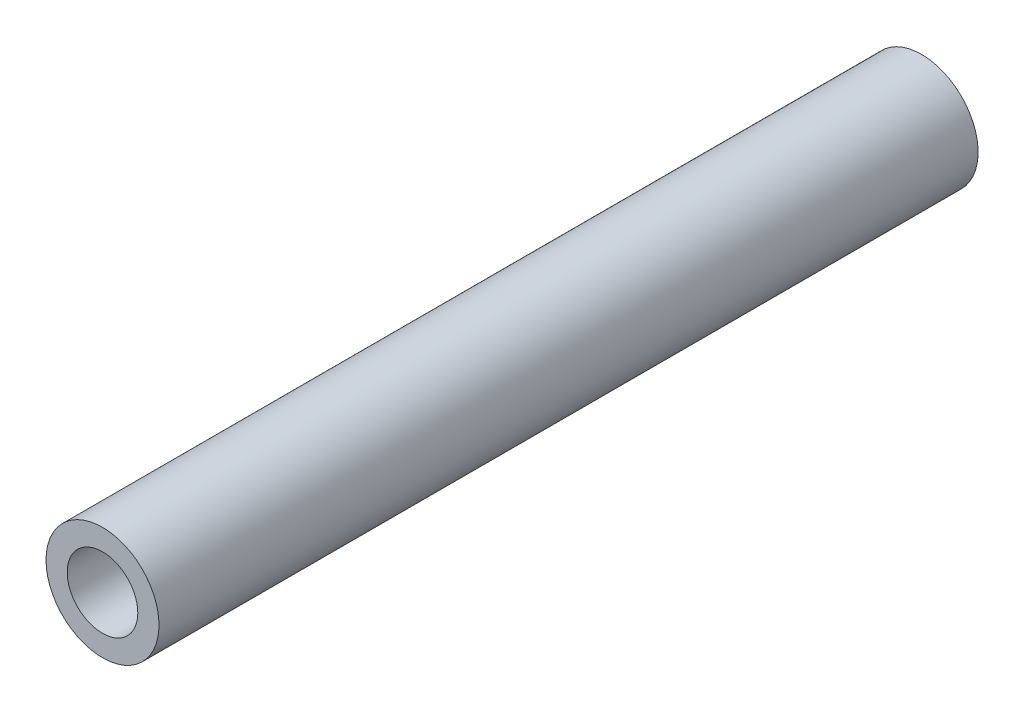
SolidWorks part; units mm, degrees
material "1060 Alloy"
ref_plane "Front Plane" through (0, 0, 0) normal (0, 0, 1) x (1, 0, 0)
ref_plane "Top Plane" through (0, 0, 0) normal (0, 1, 0) x (1, 0, 0)
ref_plane "Right Plane" through (0, 0, 0) normal (1, 0, 0) x (0, 0, -1)
sketch "Sketch1" plane through (0, 0, 0) normal (0, 0, 1) x (1, 0, 0)
  circle A0 centre (0, 0) radius 2
  dimension "D1" = 4
extrude "Boss-Extrude1" add sketch "Sketch1" along normal blind 29
ref_plane "Plane1" through (0, 0, 14.5) normal (0, 0, -1) x (-1, 0, 0)
sketch "Sketch3" plane through (0, 0, 29) normal (0, 0, 1) x (1, 0, 0)
  line L1 (3, 0) -> (1.5, 2.5981)
  line L2 (1.5, 2.5981) -> (-1.5, 2.5981)
  line L3 (-1.5, 2.5981) -> (-3, 0)
  line L4 (-3, 0) -> (-1.5, -2.5981)
  line L5 (-1.5, -2.5981) -> (1.5, -2.5981)
  line L6 (1.5, -2.5981) -> (3, 0)
  circle A0 centre (0, 0) radius 2.5981 construction
  circle M7 centre (0, 0) radius 2
extrude "Cut-Extrude1" [suppressed] cut sketch "Sketch3" against normal blind 5 contours L3 M7 | L1 M7 | L2 M7 | L4 M7 | L5 M7 | L6 M7
mirror "Mirror1" [suppressed] about plane through (0, 0, 14.5) normal (0, 0, -1)
hole_wizard "Tap Drill for M3x0.5 Tap1" positions "Sketch4" profile "Sketch6" hole size "M3x0.5" standard "ANSI Metric"
sketch "Sketch4" plane through (0, 0, 29) normal (0, 0, 1) x (1, 0, 0)
  point P0 (0, 0)
sketch "Sketch6" plane through (0, 0, 29) normal (1, 0, 0) x (0, -1, 0)
  line L0 (0, 0) -> (0, 5.7511)
  line L1 (0, 5.7511) -> (1.25, 5)
  line L2 (1.25, 5) -> (1.25, 0)
  line L5 (1.25, 0) -> (0, 0)
  line L10 (0, 5.7511) -> (-1.25, 5) construction
  line L11 (0, -6.35) -> (0, 107.95) construction
  dimension "Hole Dia." = 2.5
  dimension "Hole Depth" = 5
  dimension "Drill Angle" = 118
mirror "Mirror2" about plane through (0, 0, 14.5) normal (0, 0, -1) of "Tap Drill for M3x0.5 Tap1"
